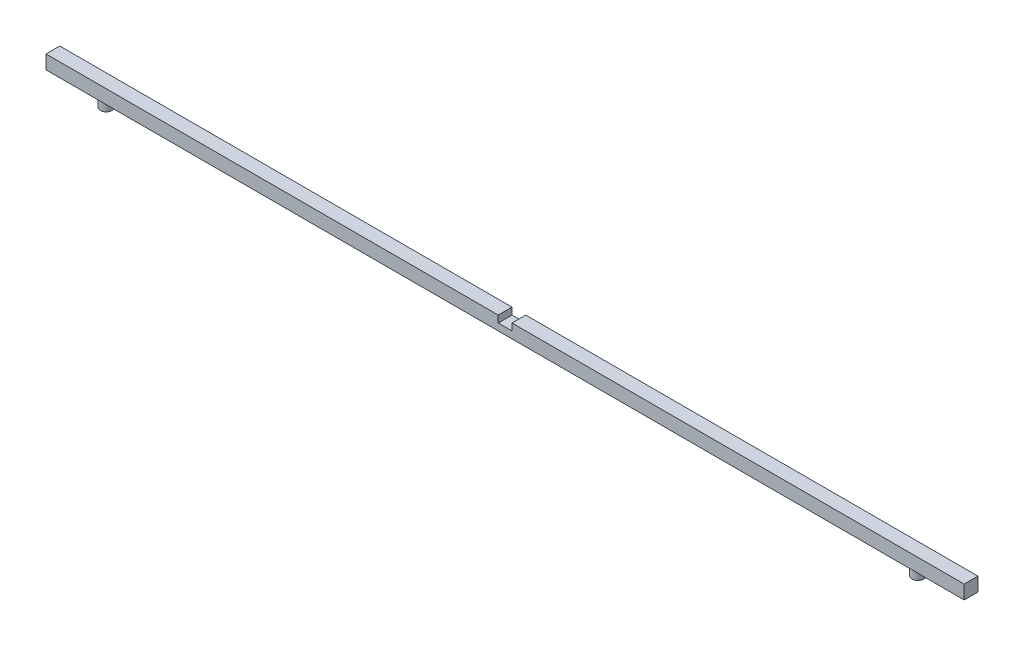
SolidWorks part; units mm, degrees
ref_plane "前视基准面" through (0, 0, 0) normal (0, 0, 1) x (1, 0, 0)
ref_plane "上视基准面" through (0, 0, 0) normal (0, 1, 0) x (1, 0, 0)
ref_plane "右视基准面" through (0, 0, 0) normal (1, 0, 0) x (0, 0, -1)
sketch "草图1" plane through (0, 0, 0) normal (0, 0, 1) x (1, 0, 0)
  line L0 (0, 345.8717) -> (0, -301.9404) construction
  line L1 (-1000, 30) -> (-15, 30)
  line L2 (-1000, 30) -> (-1000, 0)
  line L3 (-1000, 0) -> (1000, 0)
  line L4 (1000, 30) -> (1000, 0)
  line L5 (-15, 30) -> (-15, 15)
  line L6 (-15, 15) -> (15, 15)
  line L7 (15, 15) -> (15, 30)
  line L8 (15, 30) -> (1000, 30)
  point P11 (1000, 15)
  dimension "D1" = 2000
  dimension "D2" = 30
  dimension "D3" = 30
  dimension "D4" = 15
extrude "凸台-拉伸1" add sketch "草图1" along normal blind 30
sketch "草图3" plane through (0, 0, 0) normal (0, -1, 0) x (1, 0, 0)
  line L0 (0, 169.4472) -> (0, -201.1092) construction
  line L1 (-1000, 0) -> (1000, 0) construction
  circle A0 centre (-883.8835, 15) radius 10
  circle A1 centre (883.8835, 15) radius 10
  dimension "D1" = 20
  dimension "D2" = 15
  dimension "D3" = 1767.767
extrude "切除-拉伸1" cut sketch "草图3" against normal blind 15
sketch "草图4" plane through (0, 0, 0) normal (0, -1, 0) x (1, 0, 0)
  line L0 (0, 207.2327) -> (0, -291.7768) construction
  circle A0 centre (-883.8835, 15) radius 12.5
  circle A1 centre (-883.8835, 15) radius 10 construction
  circle A2 centre (883.8835, 15) radius 12.5
  circle A3 centre (-883.8835, 15) radius 10
  circle A4 centre (883.8835, 15) radius 10
  dimension "D1" = 25
extrude "凸台-拉伸2" add sketch "草图4" along normal blind 20
